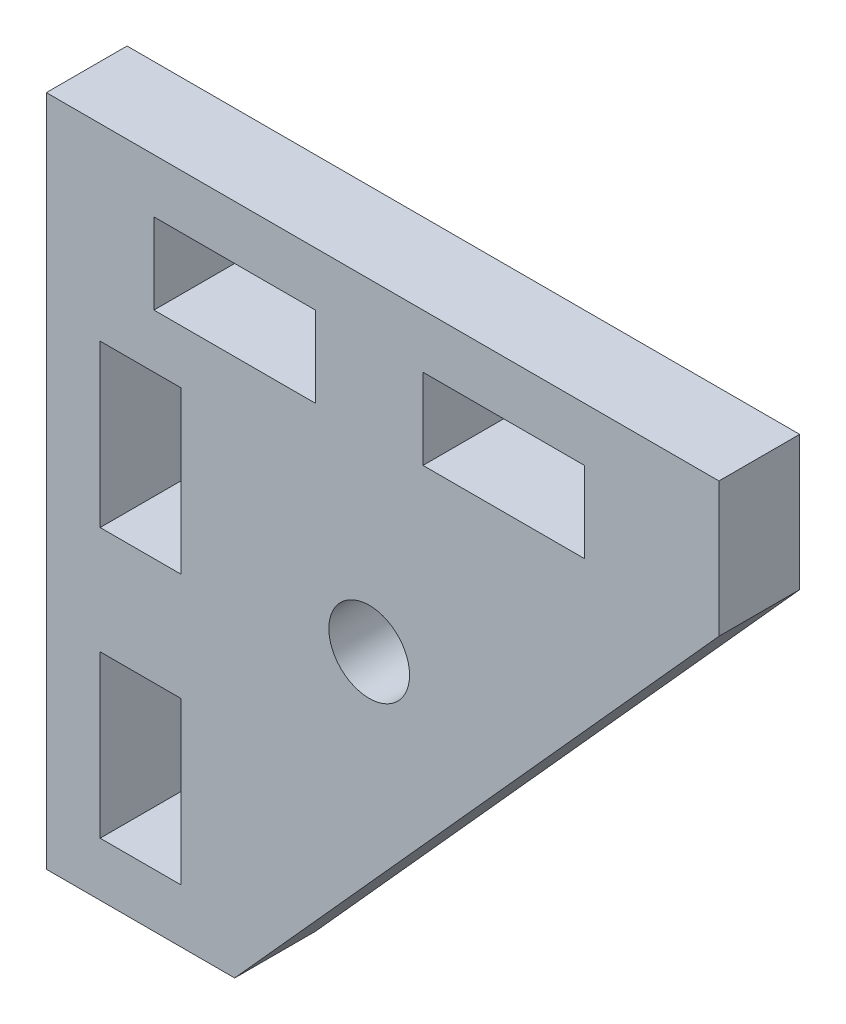
SolidWorks part; units mm, degrees
material "Thornel Mat VMA"
ref_plane "前视基准面" through (0, 0, 0) normal (0, 0, 1) x (1, 0, 0)
ref_plane "上视基准面" through (0, 0, 0) normal (0, 1, 0) x (1, 0, 0)
ref_plane "右视基准面" through (0, 0, 0) normal (1, 0, 0) x (0, 0, -1)
sketch "草图1" plane through (0, 0, 0) normal (0, 0, 1) x (1, 0, 0)
  line L0 (0, 0) -> (0, -2)
  line L2 (0, -13.75) -> (0, 13.75) construction
  line L16 (0, 0) -> (25, 0)
  line L17 (13.75, 0) -> (-13.75, 0) construction
  line L18 (0, -25) -> (7, -25)
  line L19 (2, -7) -> (5, -7)
  line L20 (2, -7) -> (2, -13)
  line L21 (2, -13) -> (5, -13)
  line L22 (5, -7) -> (5, -13)
  line L27 (2, -17) -> (5, -17)
  line L28 (2, -17) -> (2, -23)
  line L29 (2, -23) -> (5, -23)
  line L30 (5, -17) -> (5, -23)
  line L35 (25, 0) -> (25, -5)
  line L36 (25, -5) -> (7, -25)
  line L43 (0, -5) -> (0, -25)
  line L44 (0, -2) -> (0, -5)
  line L45 (14, -2) -> (14, -5)
  line L46 (4, -2) -> (10, -2)
  line L47 (4, -2) -> (4, -5)
  line L48 (4, -5) -> (10, -5)
  line L49 (10, -2) -> (10, -5)
  line L50 (14, -2) -> (20, -2)
  line L51 (20, -2) -> (20, -5)
  line L52 (14, -5) -> (20, -5)
  dimension "D1" = 3
  dimension "D2" = 6
  dimension "D3" = 7
  dimension "D5" = 25
  dimension "D4" = 2
  dimension "D6" = 25
  dimension "D7" = 6
  dimension "D8" = 3
  dimension "D9" = 4
  dimension "D10" = 6
  dimension "D11" = 4
  dimension "D12" = 5
  dimension "D13" = 7
extrude "凸台-拉伸1" add sketch "草图1" along normal blind 3
sketch "草图2" plane through (0, 0, 3) normal (0, 0, 1) x (1, 0, 0)
  line L0 (1.65, 0) -> (-1.65, 0) construction
  line L2 (0, -1.65) -> (0, 1.65) construction
  circle A0 centre (12, -12) radius 1.5
  point P6 (0, -13.6249)
  point P9 (15.1714, -15.9206)
  dimension "D1" = 12
  dimension "D2" = 12
extrude "切除-拉伸1" cut sketch "草图2" against normal blind 10
